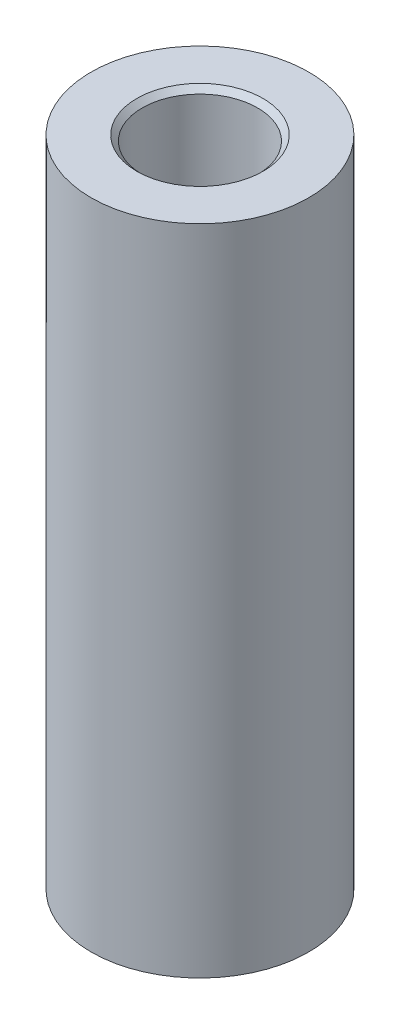
SolidWorks part; units mm, degrees
material "AISI 1045 Steel, cold drawn"
ref_plane "Front Plane" through (0, 0, 0) normal (0, 0, 1) x (1, 0, 0)
ref_plane "Top Plane" through (0, 0, 0) normal (0, 1, 0) x (1, 0, 0)
ref_plane "Right Plane" through (0, 0, 0) normal (1, 0, 0) x (0, 0, -1)
sketch "Sketch1" plane through (0, 0, 0) normal (0, 1, 0) x (1, 0, 0)
  circle A0 centre (0, 0) radius 5
  dimension "D1" = 10
extrude "Boss-Extrude1" add sketch "Sketch1" along normal mid plane 30
hole_wizard "M5 Clearance Hole1" positions "Sketch2" profile "Sketch3" hole size "M5" standard "ANSI Metric" end condition through all
sketch "Sketch2" plane through (0, 15, 0) normal (0, 1, 0) x (1, 0, 0)
  point P0 (0, 0)
sketch "Sketch3" plane through (0, 15, 0) normal (1, 0, 0) x (0, 0, 1)
  line L0 (0, 0) -> (0, 30)
  line L1 (0, 30) -> (2.65, 30)
  line L2 (2.65, 30) -> (2.65, 0)
  line L5 (2.65, 0) -> (0, 0)
  line L11 (0, -6.35) -> (0, 107.95) construction
  dimension "Thru Hole Dia." = 5.3
  dimension "Thru Hole Depth" = 30
chamfer "Chamfer1" distance 0.25 angle 45 2 edges at (0, 15, 2.65) (0, -15, 2.65)
